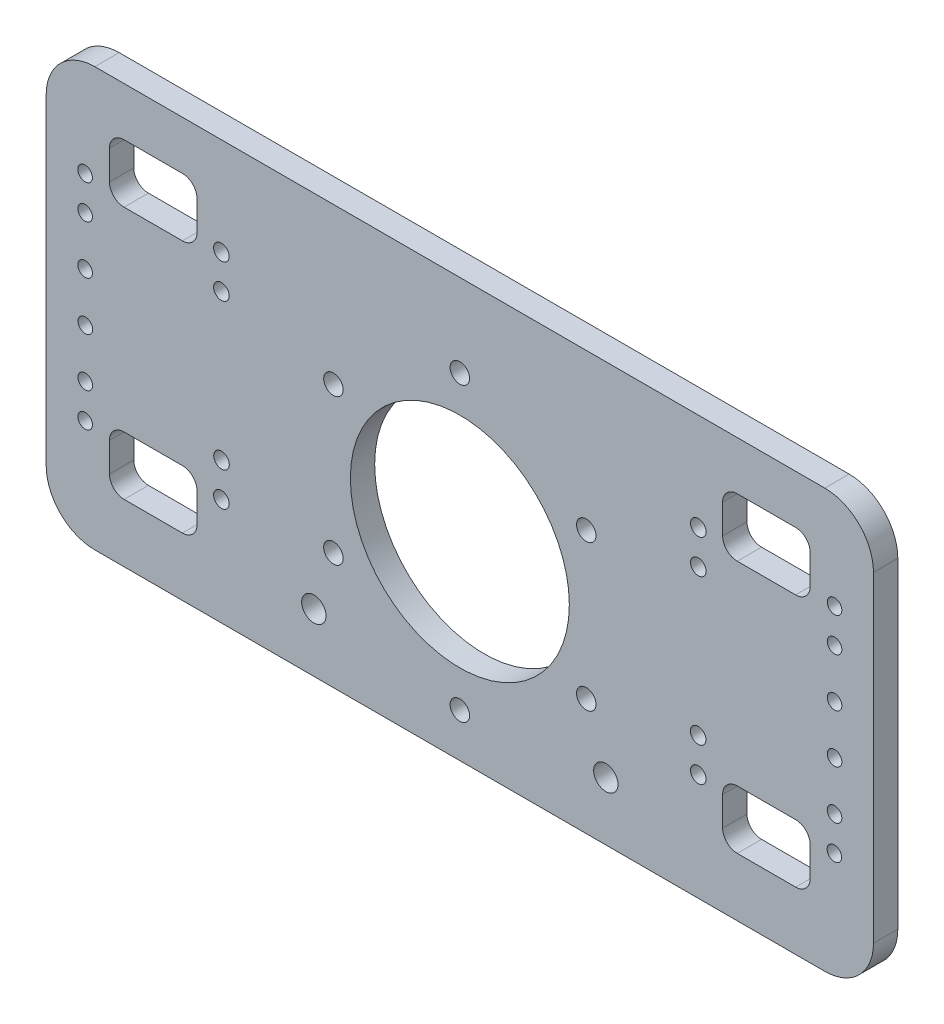
SolidWorks part; units mm, degrees
ref_plane "前视基准面" through (0, 0, 0) normal (0, 0, 1) x (1, 0, 0)
ref_plane "上视基准面" through (0, 0, 0) normal (0, 1, 0) x (1, 0, 0)
ref_plane "右视基准面" through (0, 0, 0) normal (1, 0, 0) x (0, 0, -1)
other "质心 (COM)"
sketch "草图1" plane through (0, 0, 0) normal (0, 0, 1) x (1, 0, 0)
  line L1 (-85, -50) -> (85, -50)
  line L2 (-85, -50) -> (-85, 50)
  line L3 (-85, 50) -> (85, 50)
  line L4 (85, -50) -> (85, 50)
  line L5 (-85, -50) -> (85, 50) construction
  line L6 (-85, 50) -> (85, -50) construction
  point P0 (0, 0)
  dimension "D1" = 170
  dimension "D2" = 100
extrude "凸台-拉伸1" add sketch "草图1" along normal blind 5
sketch "草图3" plane through (0, 0, 5) normal (0, 0, 1) x (1, 0, 0)
  line L0 (-85, 50) -> (-85, -50) construction
  line L1 (85, -50) -> (85, 50) construction
  circle A0 centre (-77, 22) radius 1.5
  circle A1 centre (-77, -22) radius 1.5
  circle A2 centre (77, 22) radius 1.5
  circle A3 centre (76.9722, -22) radius 1.5
  circle A4 centre (-77, 15) radius 1.5
  circle A5 centre (-77, 5) radius 1.5
  circle A6 centre (-76.9546, -4.9999) radius 1.5
  circle A7 centre (-76.9737, -14.9999) radius 1.5
  circle A8 centre (77, 15) radius 1.5
  circle A9 centre (77, 5) radius 1.5
  circle A10 centre (77.0001, -5) radius 1.5
  circle A11 centre (76.996, -15) radius 1.5
  dimension "D1" = 44
  dimension "D2" = 44
  dimension "D3" = 8
  dimension "D4" = 8
  dimension "D5" = 3
  dimension "D6" = 3
  dimension "D7" = 3
  dimension "D8" = 3
  dimension "D9" = 8
  dimension "D10" = 22
  dimension "D11" = 7
  dimension "D12" = 10
  dimension "D13" = 10
  dimension "D14" = 10
  dimension "D15" = 3
  dimension "D16" = 3
  dimension "D17" = 3
  dimension "D18" = 3
  dimension "D19" = 7
  dimension "D20" = 10
  dimension "D21" = 10
  dimension "D22" = 10
  dimension "D23" = 3
  dimension "D24" = 3
  dimension "D25" = 3
  dimension "D26" = 3
  dimension "D27" = 22
  dimension "D28" = 8
  dimension "D29" = 8
extrude "切除-拉伸2" cut sketch "草图3" against normal through all
sketch "草图5" plane through (0, 0, 5) normal (0, 0, 1) x (1, 0, 0)
  circle A0 centre (0, -5) radius 22.5
  dimension "D1" = 5
  dimension "D2" = 45
extrude "切除-拉伸4" cut sketch "草图5" against normal through all
sketch "草图6" plane through (0, 0, 5) normal (0, 0, 1) x (1, 0, 0)
  line L0 (-85, -44) -> (85, -44)
  line L1 (-85, 50) -> (-85, -50) construction
  line L2 (85, -50) -> (85, 50) construction
  line L3 (85, -44) -> (85, -50)
  line L4 (85, -50) -> (-85, -50)
  line L5 (-85, -50) -> (-85, -44)
  dimension "D1" = 6
extrude "切除-拉伸5" cut sketch "草图6" against normal through all
sketch "草图7" plane through (0, 0, 5) normal (0, 0, 1) x (1, 0, 0)
  line L0 (85, -44) -> (-85, -44) construction
  circle A0 centre (30, -32) radius 2.5
  circle A1 centre (-30, -32) radius 2.5
  dimension "D1" = 5
  dimension "D2" = 5
  dimension "D4" = 30
  dimension "D5" = 12
  dimension "D6" = 12
  dimension "D3" = 30
extrude "切除-拉伸6" cut sketch "草图7" against normal through all
sketch "草图8" plane through (0, 0, 5) normal (0, 0, 1) x (1, 0, 0)
  line L0 (-85, 32) -> (85, 32)
  line L1 (-85, 50) -> (-85, -44) construction
  line L2 (85, -44) -> (85, 50) construction
  line L3 (85, 32) -> (85, 50)
  line L4 (85, 50) -> (-85, 50)
  line L5 (-85, 50) -> (-85, 32)
  dimension "D1" = 18
extrude "切除-拉伸7" cut sketch "草图8" against normal blind 10
sketch "草图9" plane through (0, 0, 5) normal (0, 0, 1) x (1, 0, 0)
  line L0 (-72, 32) -> (-72, 20)
  line L1 (-85, 32) -> (85, 32) construction
  line L2 (-72, 20) -> (-54, 20)
  line L3 (-54, 20) -> (-54, 32)
  line L4 (-54, 32) -> (-72, 32)
  line L5 (-85, 32) -> (-85, -44) construction
  line L6 (85, -44) -> (85, 32) construction
  line L7 (54, 32) -> (72, 32)
  line L8 (54, 20) -> (54, 32)
  line L9 (72, 20) -> (54, 20)
  line L10 (72, 32) -> (72, 20)
  dimension "D1" = 13
  dimension "D2" = 12
  dimension "D3" = 31
  dimension "D4" = 12
  dimension "D5" = 0
  dimension "D6" = 13
  dimension "D7" = 31
extrude "切除-拉伸9" cut sketch "草图9" against normal blind 10
sketch "草图10" plane through (0, 0, 5) normal (0, 0, 1) x (1, 0, 0)
  line L0 (-72, -20) -> (-54, -20)
  line L1 (-54, -20) -> (-54, -32)
  line L2 (-54, -32) -> (-72, -32)
  line L3 (-72, -32) -> (-72, -20)
  line L4 (85, -44) -> (-85, -44) construction
  line L5 (-85, 32) -> (-85, -44) construction
  line L6 (0, -44) -> (0, -17.62)
  line L7 (72, -32) -> (72, -20)
  line L8 (54, -32) -> (72, -32)
  line L9 (54, -20) -> (54, -32)
  line L10 (72, -20) -> (54, -20)
  dimension "D1" = 18
  dimension "D2" = 24
  dimension "D3" = 12
  dimension "D4" = 13
extrude "切除-拉伸10" cut sketch "草图10" against normal blind 10 contours L3 L2 L1 L0 | L7 L10 L9 L8
fillet "圆角3" radius 3 12 edges at (-54, -20, 2.5) (-72, -20, 2.5) (-54, -32, 2.5) (-72, -32, 2.5) (72, -32, 2.5) (54, -32, 2.5) (72, -20, 2.5) (54, -20, 2.5) (72, 20, 2.5) (54, 20, 2.5) (-54, 20, 2.5) (-72, 20, 2.5)
sketch "草图11" plane through (0, 32, 0) normal (0, 1, 0) x (1, 0, 0)
  line L0 (-85, 0) -> (85, 0)
  line L1 (85, 0) -> (85, -5)
  line L2 (85, -5) -> (-85, -5)
  line L3 (-85, 0) -> (-85, -5) construction
  line L4 (-85, -5) -> (-85, 0)
extrude "凸台-拉伸2" add sketch "草图11" along normal blind 10
fillet "圆角4" radius 3 4 edges at (72, 32, 2.5) (54, 32, 2.5) (-54, 32, 2.5) (-72, 32, 2.5)
fillet "圆角5" radius 10 4 edges at (85, -44, 2.5) (-85, -44, 2.5) (-85, 42, 2.5) (85, 42, 2.5)
sketch "草图12" plane through (0, 0, 5) normal (0, 0, 1) x (1, 0, 0)
  line L0 (-69, 20) -> (-57, 20) construction
  line L1 (-69, -20) -> (-57, -20) construction
  line L2 (0, 42) -> (0, 17.5)
  line L3 (-75, 42) -> (75, 42) construction
  circle A0 centre (-49, 22) radius 1.6
  circle A1 centre (-49, 15) radius 1.6
  circle A2 centre (-48.9737, -15) radius 1.6
  circle A3 centre (-49, -22) radius 1.6
  circle A4 centre (-77, 22) radius 1.5 construction
  circle A5 centre (-77, 15) radius 1.5 construction
  circle A6 centre (-76.9737, -14.9999) radius 1.5 construction
  circle A7 centre (-77, -22) radius 1.5 construction
  circle A8 centre (0, -5) radius 22.5 construction
  circle A9 centre (49, -22) radius 1.6
  circle A10 centre (48.9737, -15) radius 1.6
  circle A11 centre (49, 15) radius 1.6
  circle A12 centre (49, 22) radius 1.6
  dimension "D1" = 28
  dimension "D2" = 28
  dimension "D3" = 2
  dimension "D4" = 7
  dimension "D5" = 28
  dimension "D6" = 28
  dimension "D7" = 7
  dimension "D8" = 2
  dimension "D9" = 3.2
  dimension "D10" = 3.2
  dimension "D11" = 3.2
  dimension "D12" = 3.2
extrude "切除-拉伸11" cut sketch "草图12" against normal through all contours A0 | A1 | A2 | A3 | A12 | A11 | A10 | A9
sketch "草图13" plane through (0, 0, 5) normal (0, 0, 1) x (1, 0, 0)
  circle A0 centre (0, -5) radius 30
  circle A1 centre (0, 25) radius 2
  circle A2 centre (25.9808, 10) radius 2
  circle A3 centre (25.9808, -20) radius 2
  circle A4 centre (0, -35) radius 2
  circle A5 centre (-25.9808, -20) radius 2
  circle A6 centre (-25.9808, 10) radius 2
  point P17 (0, -5)
  point P18 (8.6603, 0)
  dimension "D1" = 60
  dimension "D2" = 4
  dimension "D3" = 6
extrude "切除-拉伸12" cut sketch "草图13" against normal blind 17
